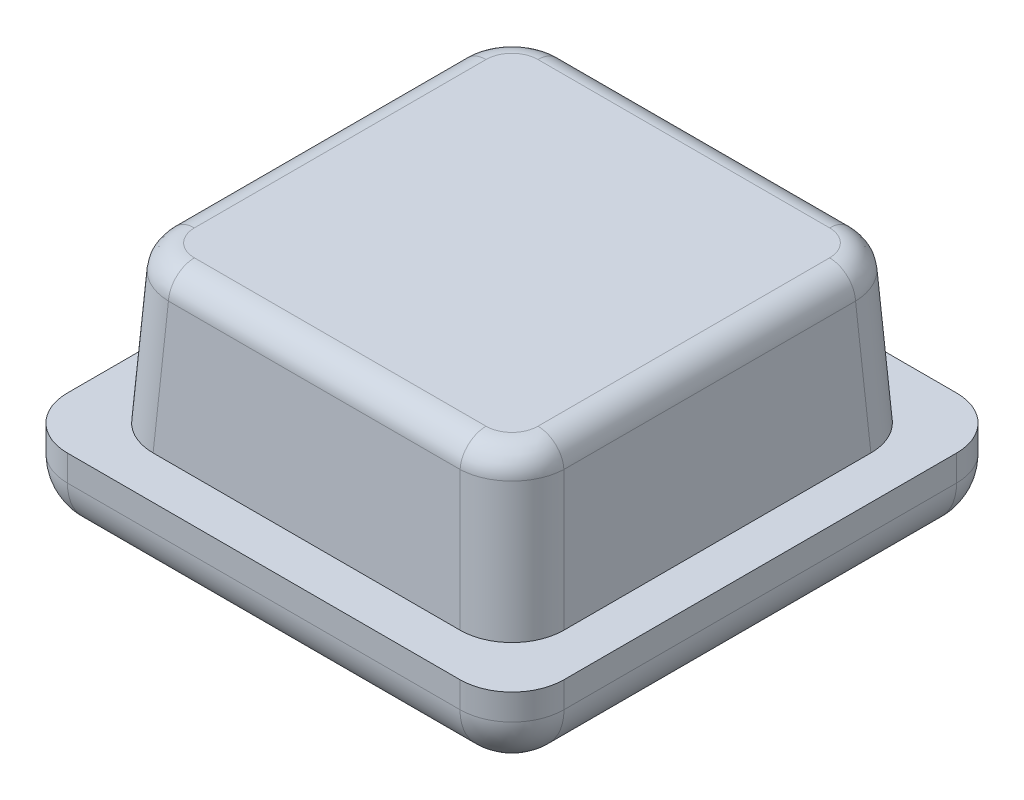
SolidWorks part; units mm, degrees
ref_plane "Front Plane" through (0, 0, 0) normal (0, 0, 1) x (1, 0, 0)
ref_plane "Top Plane" through (0, 0, 0) normal (0, 1, 0) x (1, 0, 0)
ref_plane "Right Plane" through (0, 0, 0) normal (1, 0, 0) x (0, 0, -1)
sketch "Sketch1" plane through (0, 0, 0) normal (0, 1, 0) x (1, 0, 0)
  line L1 (0, 0) -> (19.1, 0)
  line L2 (0, 0) -> (0, 19.1)
  line L3 (0, 19.1) -> (19.1, 19.1)
  line L4 (19.1, 0) -> (19.1, 19.1)
  dimension "D1" = 19.1
extrude "Boss-Extrude1" add sketch "Sketch1" along normal blind 3
sketch "Sketch2" plane through (0, 3, 0) normal (0, 1, 0) x (1, 0, 0)
  line L8 (1.65, 1.65) -> (17.45, 1.65)
  line L9 (17.45, 1.65) -> (17.45, 17.45)
  line L10 (1.65, 17.45) -> (1.65, 1.65)
  line L11 (17.45, 17.45) -> (1.65, 17.45)
  line L12 (1.65, 1.65) -> (17.45, 1.65)
  line L13 (17.45, 1.65) -> (17.45, 17.45)
  line L14 (1.65, 17.45) -> (1.65, 1.65)
  line L15 (17.45, 17.45) -> (1.65, 17.45)
  dimension "D1" = 1.65
ref_plane "Plane1" through (0, 9, 0) normal (0, 1, 0) x (1, 0, 0)
sketch "Sketch3" plane through (0, 9, 0) normal (0, 1, 0) x (1, 0, 0)
  line L8 (2, 2) -> (17.1, 2)
  line L9 (2, 17.1) -> (2, 2)
  line L10 (17.1, 17.1) -> (2, 17.1)
  line L11 (17.1, 2) -> (17.1, 17.1)
  line L12 (2, 2) -> (17.1, 2)
  line L13 (2, 17.1) -> (2, 2)
  line L14 (17.1, 17.1) -> (2, 17.1)
  line L15 (17.1, 2) -> (17.1, 17.1)
  dimension "D1" = 2
loft "Loft1" add profiles "Sketch2", "Sketch3"
ref_plane "Plane2" through (9.55, 0, 0) normal (1, 0, 0) x (0, 0, -1)
ref_plane "Plane3" through (0, 0, -9.55) normal (0, 0, 1) x (1, 0, 0)
fillet "Fillet1" radius 2 8 edges at (19.1, 1.5, 0) (0, 1.5, 0) (19.1, 1.5, -19.1) (0, 1.5, -19.1)
fillet "Fillet2" radius 1 8 edges
fillet "Fillet3" radius 2 8 edges at (0.5858, 0, -0.5858) (0, 0, -9.55) (0.5858, 0, -18.5142) (9.55, 0, -19.1) (18.5142, 0, -18.5142) (19.1, 0, -9.55) (18.5142, 0, -0.5858) (9.55, 0, 0)
